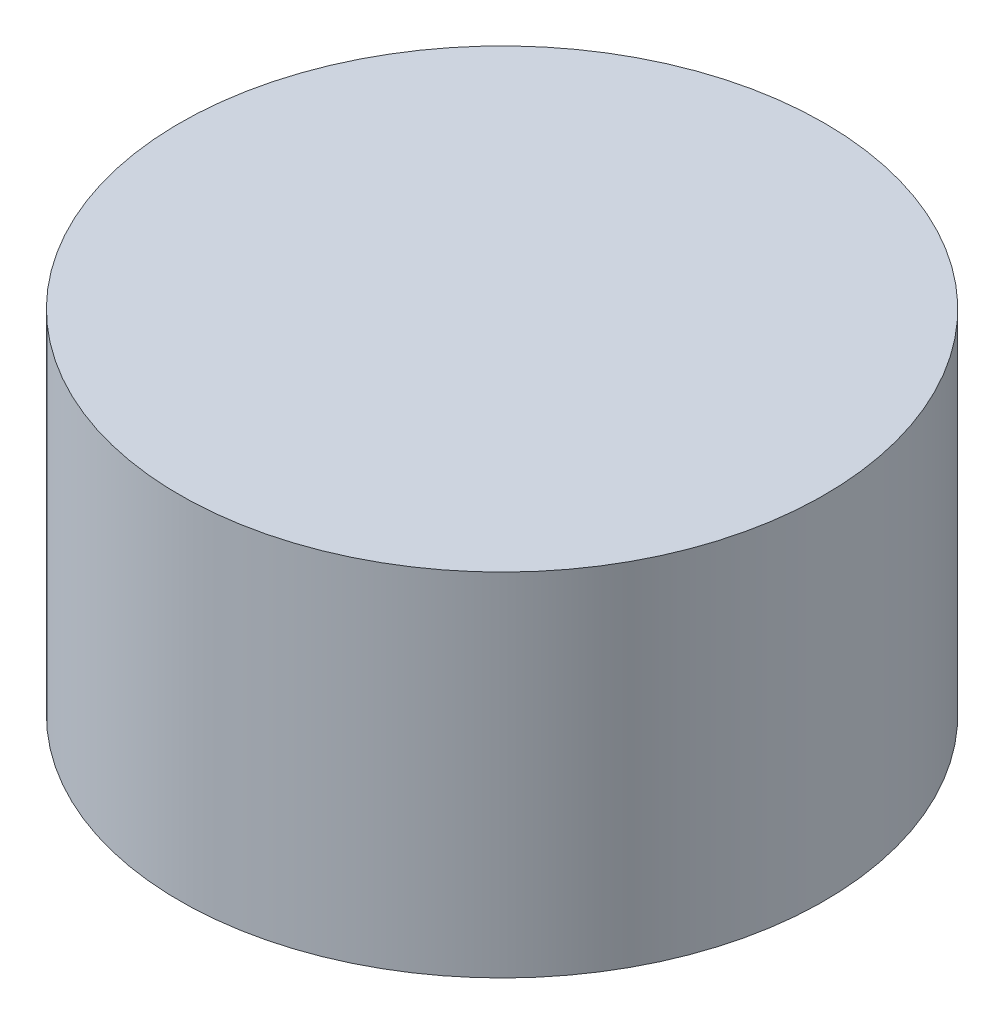
SolidWorks part; units mm, degrees
ref_plane "Ön Düzlem" through (0, 0, 0) normal (0, 0, 1) x (1, 0, 0)
ref_plane "Üst Düzlem" through (0, 0, 0) normal (0, 1, 0) x (1, 0, 0)
ref_plane "Sağ Düzlem" through (0, 0, 0) normal (1, 0, 0) x (0, 0, -1)
sketch "Sketch2" plane through (0, 0, 0) normal (0, 0, 1) x (1, 0, 0)
  line L0 (-90.2046, 88.6759) -> (-90.2046, 28.6759)
  line L1 (-90.2046, 28.6759) -> (-35.2046, 28.6759)
  line L2 (-35.2046, 28.6759) -> (-35.2046, 88.6759)
  line L3 (-35.2046, 88.6759) -> (-90.2046, 88.6759)
revolve "Revolve1" add sketch "Sketch2" angle 360 about L2
sketch "Sketch3" plane through (0, 28.6759, 0) normal (0, -1, 0) x (1, 0, 0)
  circle A0 centre (-35.2046, 0) radius 50
  circle A1 centre (-35.2046, 0) radius 55 construction
  dimension "D1" = 100
  dimension "D2" = 5
extrude "Cut-Extrude1" cut sketch "Sketch3" against normal blind 55
ref_plane "Plane1" through (-95, 0, 0) normal (1, 0, 0) x (0, 0, -1)
sketch "Sketch5" plane through (-95, 0, 0) normal (1, 0, 0) x (0, 0, -1)
  line L0 (-55, 28.6759) -> (55, 28.6759) construction
  line L2 (3.1938, 58.1759) -> (7.6938, 58.1759)
  line L3 (3.1938, 58.1759) -> (-1.3062, 58.1759)
  line L4 (7.6938, 58.1759) -> (7.6938, 67.1759)
  line L5 (7.6938, 67.1759) -> (-1.3062, 67.1759)
  line L6 (-1.3062, 67.1759) -> (-1.3062, 58.1759)
  line L7 (55, 88.6759) -> (-55, 88.6759) construction
  dimension "D1" = 21.5
  dimension "D2" = 9
  dimension "D3" = 9
  dimension "D4" = 29.5
  dimension "D5" = 4.5
  dimension "D7" = 60
extrude "Cut-Extrude2" cut sketch "Sketch5" along normal blind 55
sketch "Sketch6" plane through (0, 28.6759, 0) normal (0, -1, 0) x (-1, 0, 0)
  circle A0 centre (35.2046, -52.5096) radius 1.9981
  circle A1 centre (-17.305, 0) radius 1.9981
  circle A2 centre (35.2046, 52.5096) radius 1.9981
  circle A3 centre (87.7142, 0) radius 1.9981
  circle A4 centre (35.2046, 0) radius 50 construction
  point P11 (35.2046, 0)
  dimension "D2" = 3.9963
  dimension "D3" = 52.5096
  dimension "D1" = 4
extrude "Cut-Extrude3" cut sketch "Sketch6" against normal blind 5
